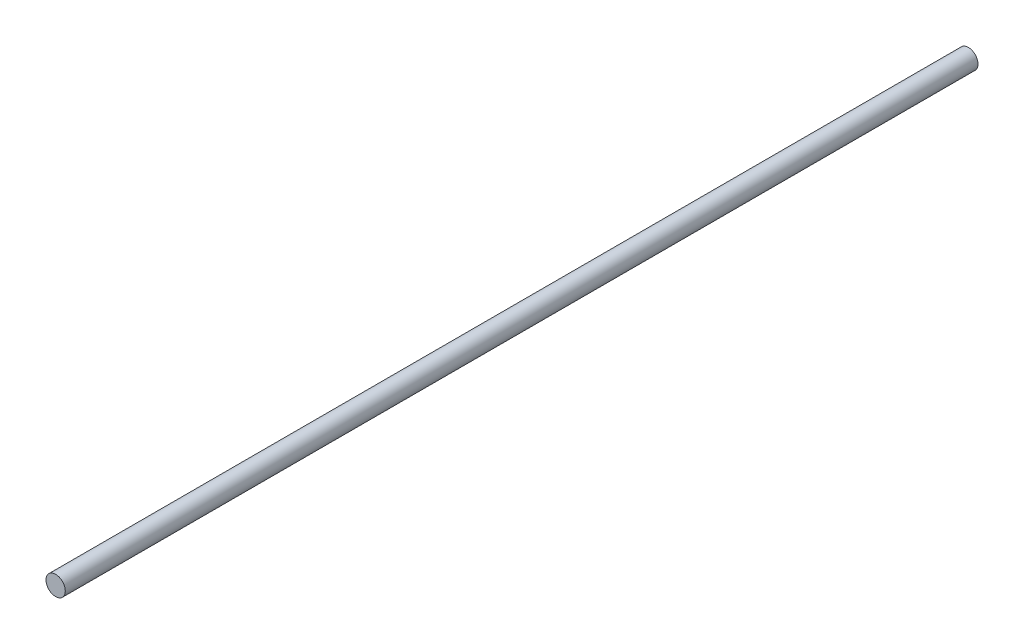
SolidWorks part; units mm, degrees
material "1.5714 (16NiCr4)"
ref_plane "Спереди" through (0, 0, 0) normal (0, 0, 1) x (1, 0, 0)
ref_plane "Сверху" through (0, 0, 0) normal (0, 1, 0) x (1, 0, 0)
ref_plane "Справа" through (0, 0, 0) normal (1, 0, 0) x (0, 0, -1)
sketch "Эскиз1" plane through (0, 0, 0) normal (0, 1, 0) x (1, 0, 0)
  line L0 (2.75, 0) -> (0, 0)
  line L1 (0, 0) -> (0, -260)
  line L2 (0, -260) -> (2.75, -260)
  line L3 (2.75, -260) -> (2.75, 0)
  line L4 (0, 0) -> (0, -260) construction
revolve "Повернуть1" add sketch "Эскиз1" angle 360 about L4
